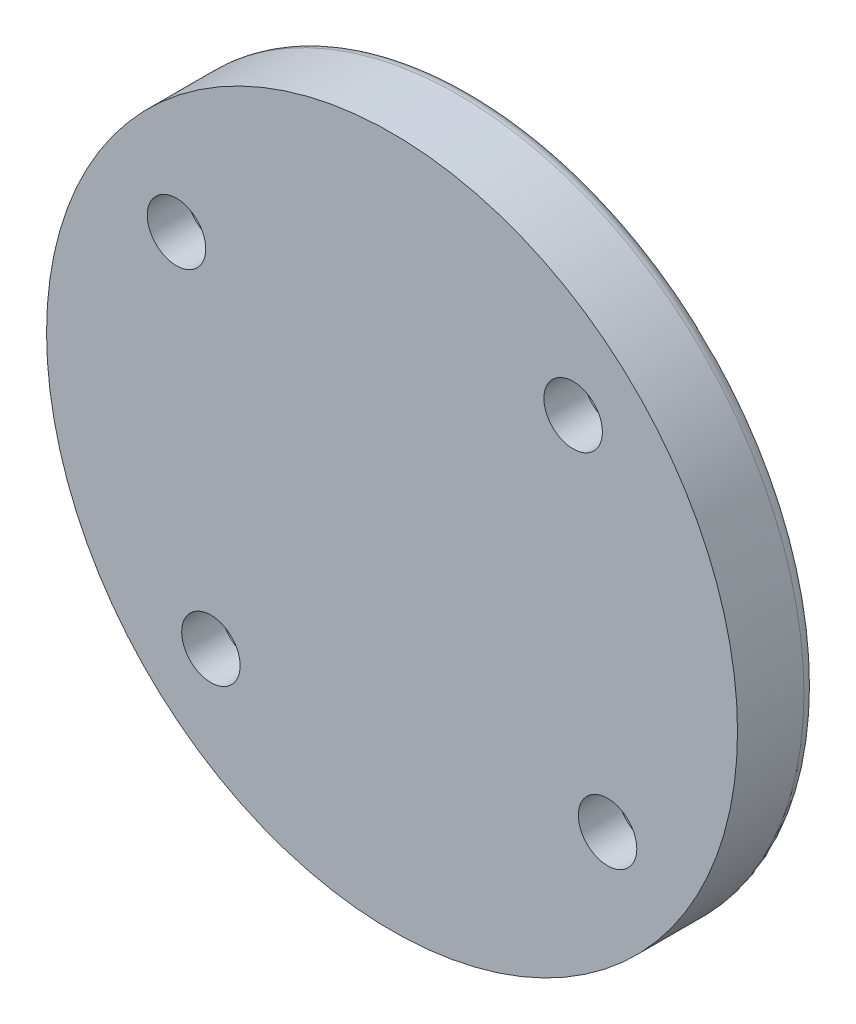
SolidWorks part; units mm, degrees
ref_plane "前视基准面" through (0, 0, 0) normal (0, 0, 1) x (1, 0, 0)
ref_plane "上视基准面" through (0, 0, 0) normal (0, 1, 0) x (1, 0, 0)
ref_plane "右视基准面" through (0, 0, 0) normal (1, 0, 0) x (0, 0, -1)
other "Configuration Table"
sketch "草图1" plane through (0, 0, 0) normal (0, 0, 1) x (1, 0, 0)
  line L0 (73.5854, -350.5682) -> (59.9551, -364.9979) construction
  line L1 (74.8805, -363.5036) -> (59.9551, -364.9979) construction
  line L2 (74.8805, -363.5036) -> (73.5854, -350.5682) construction
  line L3 (59.9551, -364.9979) -> (58.66, -352.0626) construction
  line L4 (56.3219, -353.8042) -> (60.302, -353.4057) construction
  line L6 (73.5854, -350.5682) -> (58.66, -352.0626) construction
  circle A0 centre (66.7703, -357.7831) radius 13
  circle A1 centre (59.9551, -364.9979) radius 1.1
  circle A2 centre (74.8805, -363.5036) radius 1.1
  circle A3 centre (58.66, -352.0626) radius 1.1
  circle A4 centre (73.5854, -350.5682) radius 1.1
  dimension "D1" = 26
  dimension "D2" = 2.2
  dimension "D3" = 15
  dimension "D4" = 13
  dimension "D5" = 13
  dimension "D6" = 15
extrude "凸台-拉伸1" add sketch "草图1" along normal blind 3
fillet "圆角1" radius 0.5 1 edges at (79.7703, -357.7831, 0)
sketch "草图2" plane through (0, 0, 0) normal (0, 0, -1) x (-1, 0, 0)
  circle A0 centre (-73.5854, -350.5682) radius 2.35
  circle A1 centre (-58.66, -352.0626) radius 2.35
  circle A2 centre (-59.9551, -364.9979) radius 2.35
  circle A3 centre (-74.8805, -363.5036) radius 2.35
  dimension "D1" = 4.7
  dimension "D2" = 4.7
extrude "切除-拉伸1" cut sketch "草图2" against normal blind 1.5
